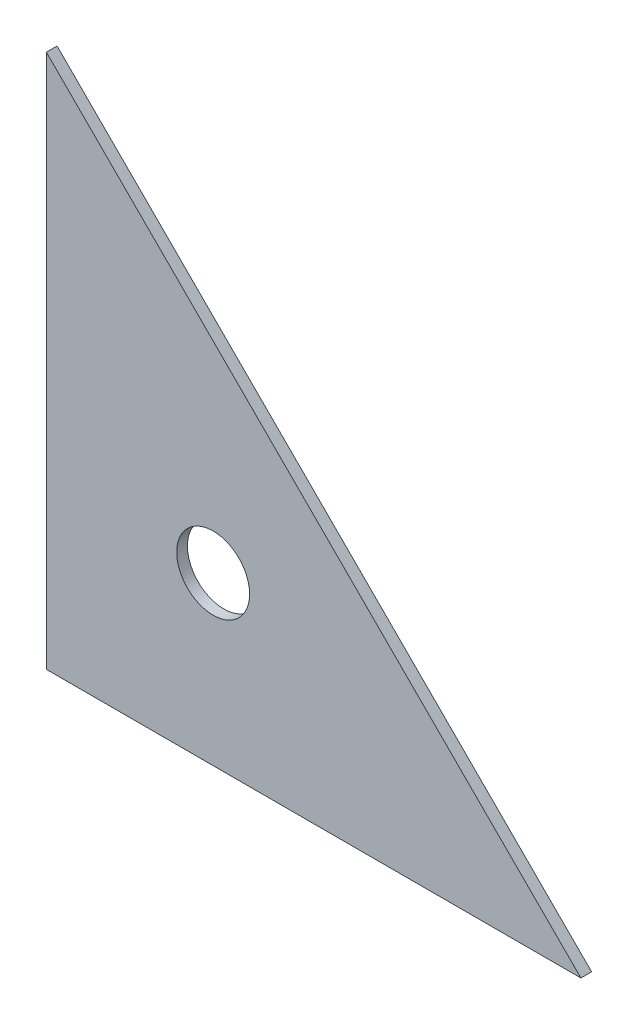
SolidWorks part; units mm, degrees
ref_plane "Front Plane" through (0, 0, 0) normal (0, 0, 1) x (1, 0, 0)
ref_plane "Top Plane" through (0, 0, 0) normal (0, 1, 0) x (1, 0, 0)
ref_plane "Right Plane" through (0, 0, 0) normal (1, 0, 0) x (0, 0, -1)
sketch "Sketch1" plane through (0, 0, 0) normal (0, 0, 1) x (1, 0, 0)
  line L0 (0, 0) -> (0, 25)
  line L1 (0, 25) -> (25, 0)
  line L2 (25, 0) -> (0, 0)
  circle A0 centre (7.8, 7.8) radius 1.705
  dimension "D3" = 3.41
  dimension "D4" = 7.8
  dimension "D5" = 7.8
  dimension "D1" = 25
  dimension "D2" = 25
extrude "Boss-Extrude1" add sketch "Sketch1" along normal blind 0.5
